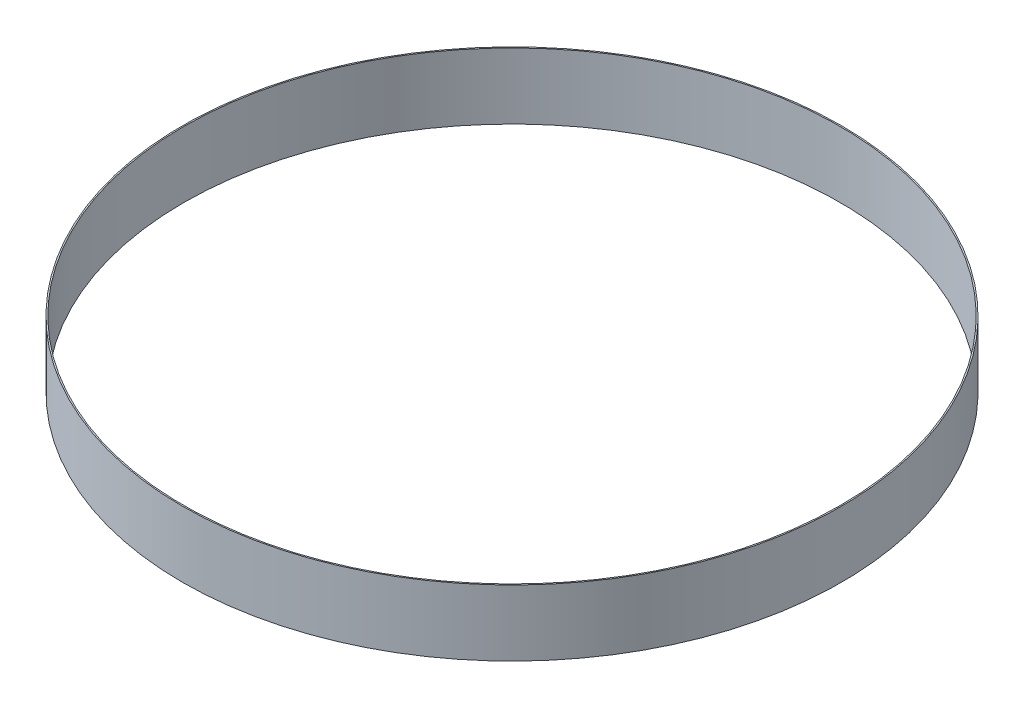
SolidWorks part; units mm, degrees
material "1060 Сплав"
ref_plane "Спереди XY" through (0, 0, 0) normal (0, 0, 1) x (1, 0, 0)
ref_plane "Сверху XZ" through (0, 0, 0) normal (0, 1, 0) x (1, 0, 0)
ref_plane "Справа ZY" through (0, 0, 0) normal (1, 0, 0) x (0, 0, -1)
sketch "Эскиз1" plane through (0, 0, 0) normal (0, 1, 0) x (1, 0, 0)
  circle A0 centre (0, 0) radius 250
  dimension "D1" = 500
extrude "Вытянуть-Тонкостенный1" add sketch "Эскиз1" along normal blind 50 thin thin type one direction reverse wall 1
